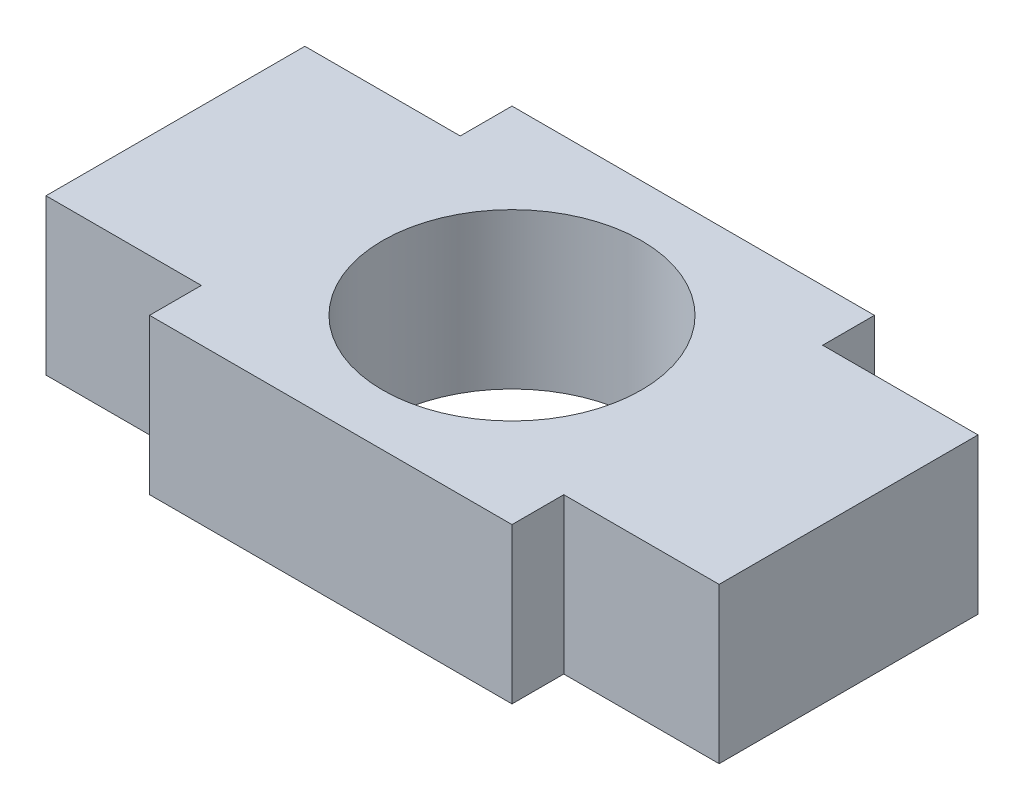
SolidWorks part; units mm, degrees
ref_plane "Plan de face" through (0, 0, 0) normal (0, 0, 1) x (1, 0, 0)
ref_plane "Plan de dessus" through (0, 0, 0) normal (0, 1, 0) x (1, 0, 0)
ref_plane "Plan de droite" through (0, 0, 0) normal (1, 0, 0) x (0, 0, -1)
sketch "Sketch1" plane through (0, 0, 0) normal (0, 1, 0) x (1, 0, 0)
  line L1 (3.5, -3.5) -> (-3.5, -3.5)
  line L2 (3.5, -3.5) -> (3.5, 3.5)
  line L3 (3.5, 3.5) -> (-3.5, 3.5)
  line L4 (-3.5, -3.5) -> (-3.5, 3.5)
  line L5 (3.5, -3.5) -> (-3.5, 3.5) construction
  line L6 (3.5, 3.5) -> (-3.5, -3.5) construction
  point P0 (0, 0)
  dimension "D1" = 7
  dimension "D2" = 7
extrude "Boss-Extrude1" add sketch "Sketch1" along normal blind 3
sketch "Sketch2" plane through (0, 3, 0) normal (0, 1, 0) x (1, 0, 0)
  circle A0 centre (0, 0) radius 2.5
  dimension "D1" = 5
extrude "Cut-Extrude1" cut sketch "Sketch2" against normal blind 3
sketch "Sketch4" plane through (0, 3, 0) normal (0, 1, 0) x (1, 0, 0)
  line L0 (-3.5, 3.5) -> (-3.5, -3.5) construction
  line L1 (-3.5, 2.5) -> (-6.5, 2.5)
  line L2 (-3.5, 2.5) -> (-3.5, -2.5)
  line L3 (-3.5, -2.5) -> (-6.5, -2.5)
  line L4 (-6.5, 2.5) -> (-6.5, -2.5)
  line L5 (3.5, 3.5) -> (-3.5, 3.5) construction
  line L7 (3.5, -3.5) -> (3.5, 3.5) construction
  line L8 (3.5, 2.5) -> (6.5, 2.5)
  line L9 (3.5, 2.5) -> (3.5, -2.5)
  line L10 (3.5, -2.5) -> (6.5, -2.5)
  line L11 (6.5, 2.5) -> (6.5, -2.5)
  dimension "D1" = 5
  dimension "D2" = 1
  dimension "D3" = 3
  dimension "D4" = 5
  dimension "D5" = 3
extrude "Boss-Extrude2" add sketch "Sketch4" against normal blind 3
